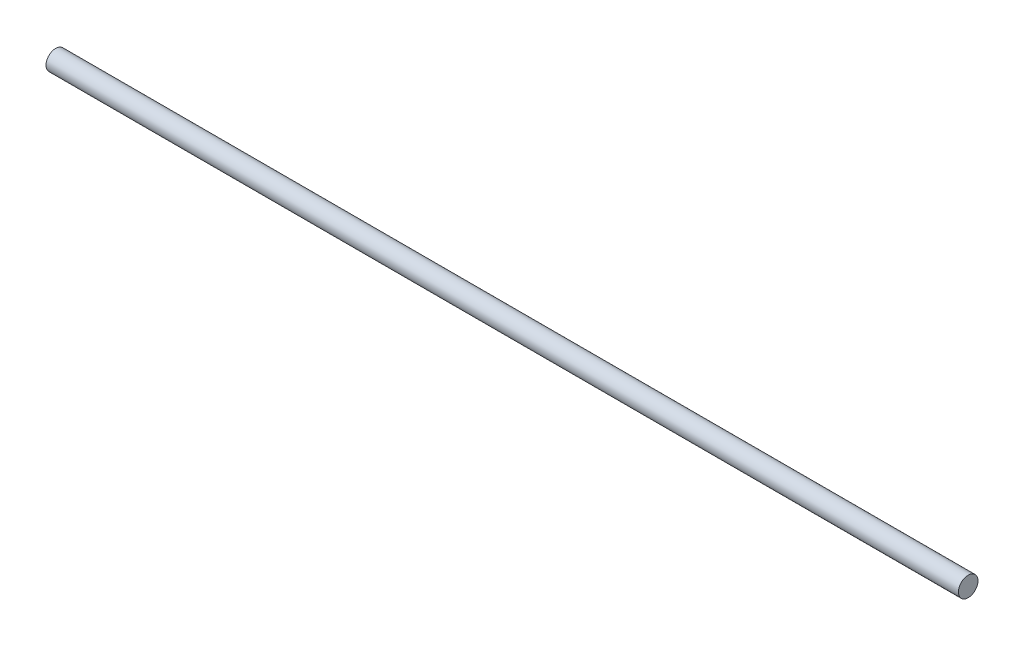
SolidWorks part; units mm, degrees
ref_plane "Front Plane" through (0, 0, 0) normal (0, 0, 1) x (1, 0, 0)
ref_plane "Top Plane" through (0, 0, 0) normal (0, 1, 0) x (1, 0, 0)
ref_plane "Right Plane" through (0, 0, 0) normal (1, 0, 0) x (0, 0, -1)
sketch "Sketch4" plane through (0, 0, 0) normal (1, 0, 0) x (0, 0, -1)
  circle A0 centre (57.6731, 144.1759) radius 3.81
  dimension "D1" = 7.62
extrude "Boss-Extrude2" add sketch "Sketch4" along normal blind 177.8 and the other way blind 177.8 separate body
